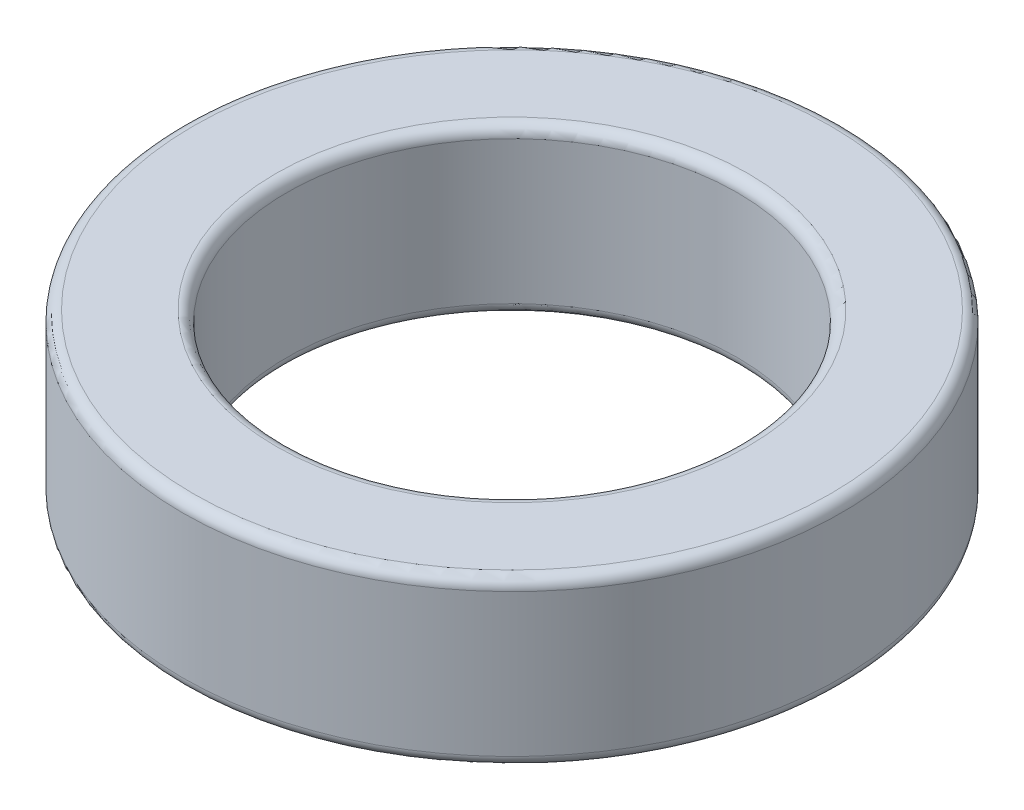
SolidWorks part; units mm, degrees
material "6061 Alloy"
ref_plane "Front Plane" through (0, 0, 0) normal (0, 0, 1) x (1, 0, 0)
ref_plane "Top Plane" through (0, 0, 0) normal (0, 1, 0) x (1, 0, 0)
ref_plane "Right Plane" through (0, 0, 0) normal (1, 0, 0) x (0, 0, -1)
sketch "Sketch1" plane through (0, 0, 0) normal (0, 1, 0) x (1, 0, 0)
  circle A0 centre (0, 0) radius 3
  circle A1 centre (0, 0) radius 2.05
  dimension "D1" = 6
  dimension "D2" = 4.1
extrude "Boss-Extrude1" add sketch "Sketch1" along normal mid plane 1.5
fillet "Fillet1" radius 0.1 4 edges at (0, -0.75, 2.05) (0, -0.75, 3) (0, 0.75, 2.05) (0, 0.75, 3)
